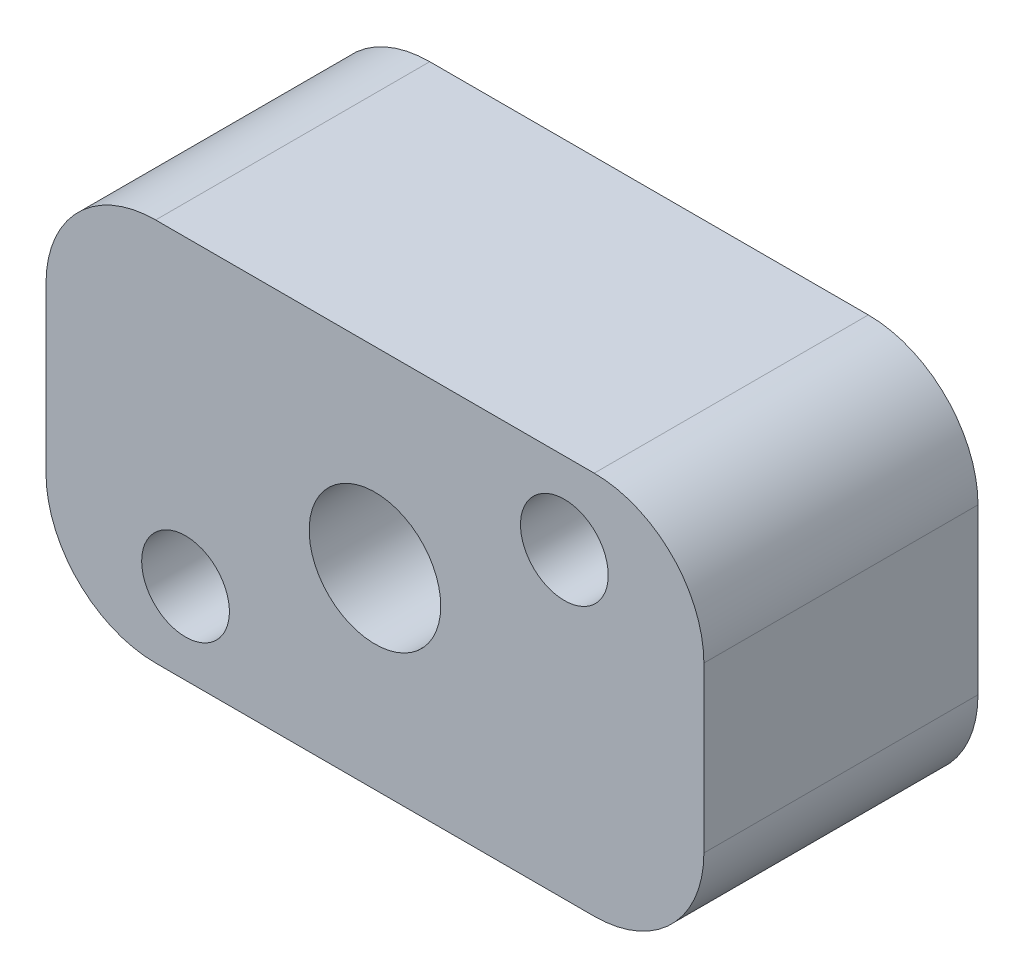
SolidWorks part; units mm, degrees
ref_plane "Plan de face" through (0, 0, 0) normal (0, 0, 1) x (1, 0, 0)
ref_plane "Plan de dessus" through (0, 0, 0) normal (0, 1, 0) x (1, 0, 0)
ref_plane "Plan de droite" through (0, 0, 0) normal (1, 0, 0) x (0, 0, -1)
sketch "Esquisse1" plane through (0, 0, 0) normal (0, 0, 1) x (1, 0, 0)
  line L0 (0, 17.5) -> (60, 17.5) construction
  line L1 (0, 0) -> (60, 0)
  line L2 (0, 0) -> (0, 35)
  line L3 (0, 35) -> (60, 35)
  line L4 (60, 0) -> (60, 35)
  line L5 (0, 0) -> (60, 35) construction
  line L6 (30, 17.5) -> (36.8732, 5.7173) construction
  circle A0 centre (30, 17.5) radius 6
  circle A1 centre (47.2756, 27.5774) radius 4
  circle A2 centre (12.7244, 7.4226) radius 4
  dimension "D3" = 12
  dimension "D4" = 40
  dimension "D5" = 8
  dimension "D1" = 35
  dimension "D2" = 60
extrude "Boss.-Extru.1" add sketch "Esquisse1" along normal blind 25
fillet "Congé1" radius 10 4 edges at (60, 0, 12.5) (0, 0, 12.5) (0, 35, 12.5) (60, 35, 12.5)
